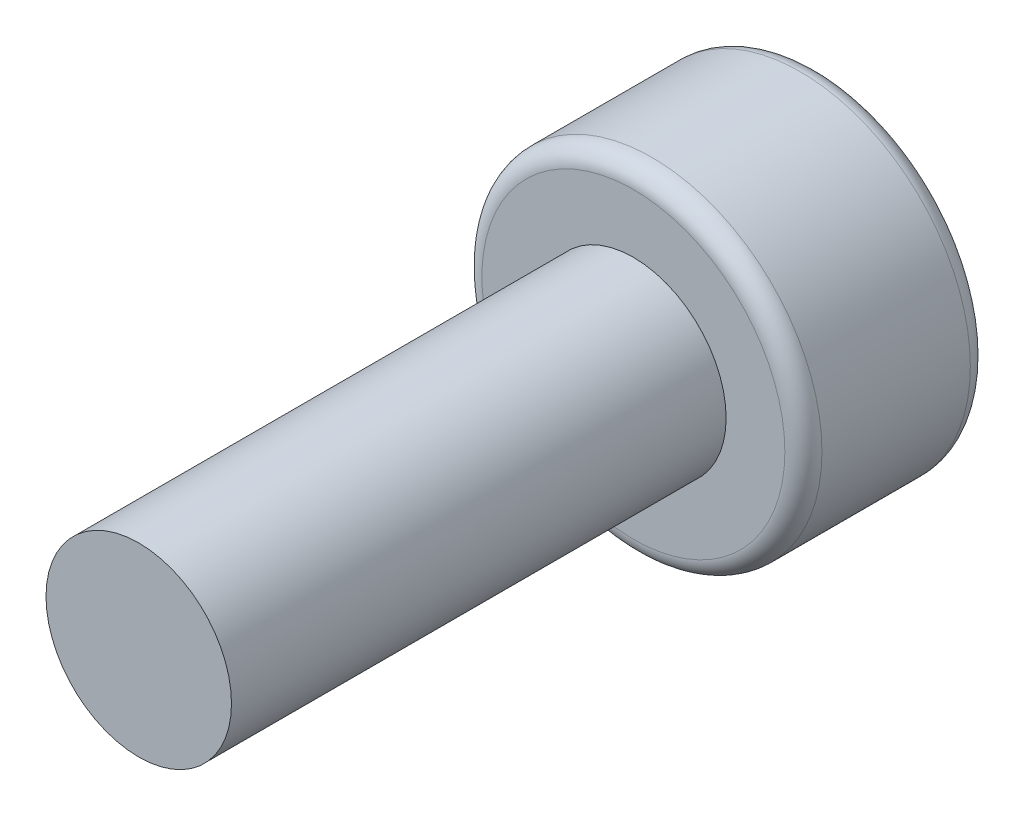
SolidWorks part; units mm, degrees
ref_plane "前视基准面" through (0, 0, 0) normal (0, 0, 1) x (1, 0, 0)
ref_plane "上视基准面" through (0, 0, 0) normal (0, 1, 0) x (1, 0, 0)
ref_plane "右视基准面" through (0, 0, 0) normal (1, 0, 0) x (0, 0, -1)
sketch "草图1" plane through (0, 0, 0) normal (0, 0, 1) x (1, 0, 0)
  circle A0 centre (0, 0) radius 2.75
  dimension "D1" = 2.75
extrude "凸台-拉伸1" add sketch "草图1" along normal blind 3
sketch "草图2" plane through (0, 0, 3) normal (0, 0, 1) x (1, 0, 0)
  circle A0 centre (0, 0) radius 1.5
  dimension "D1" = 1.5
extrude "凸台-拉伸2" add sketch "草图2" along normal blind 8
cosmetic thread "装饰螺纹线1" parameters "D2"=2
fillet "圆角1" radius 0.3 2 edges at (2.75, 0, 0) (2.75, 0, 3)
sketch "草图3" plane through (0, 0, 0) normal (0, 0, -1) x (-1, 0, 0)
  line L1 (-0.8209, 1.8624) -> (-2.0233, 0.2203)
  line L2 (-2.0233, 0.2203) -> (-1.2025, -1.6421)
  line L3 (-1.2025, -1.6421) -> (0.8209, -1.8624)
  line L4 (0.8209, -1.8624) -> (2.0233, -0.2203)
  line L5 (2.0233, -0.2203) -> (1.2025, 1.6421)
  line L6 (1.2025, 1.6421) -> (-0.8209, 1.8624)
  circle A0 centre (0, 0) radius 1.7626 construction
extrude "切除-拉伸1" cut sketch "草图3" against normal blind 2
